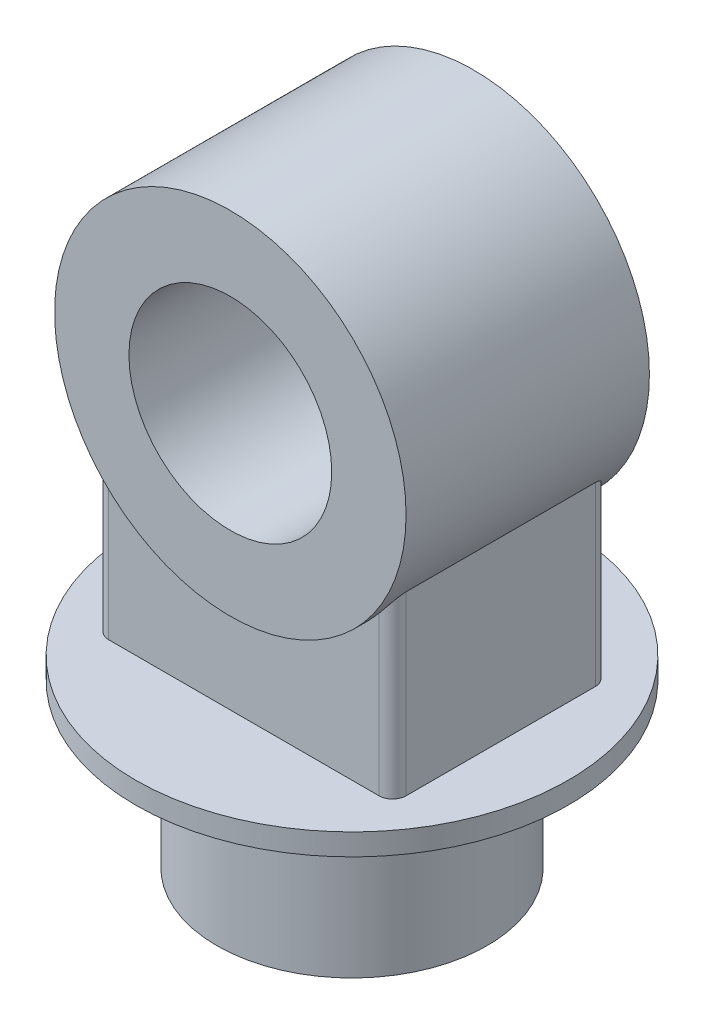
SolidWorks part; units mm, degrees
ref_plane "Front Plane" through (0, 0, 0) normal (0, 0, 1) x (1, 0, 0)
ref_plane "Top Plane" through (0, 0, 0) normal (0, 1, 0) x (1, 0, 0)
ref_plane "Right Plane" through (0, 0, 0) normal (1, 0, 0) x (0, 0, -1)
sketch "Sketch1" plane through (0, 0, 0) normal (0, 1, 0) x (1, 0, 0)
  circle A0 centre (0, 0) radius 100
  dimension "D1" = 200
extrude "Boss-Extrude1" add sketch "Sketch1" along normal blind 120 contours A0
sketch "Sketch2" plane through (0, 120, 0) normal (0, 1, 0) x (1, 0, 0)
  circle A0 centre (0, 0) radius 160
  dimension "D1" = 320
extrude "Boss-Extrude2" add sketch "Sketch2" along normal blind 16
sketch "Sketch3" plane through (0, 0, 0) normal (0, 0, 1) x (1, 0, 0)
  line L0 (160, 136) -> (-160, 136) construction
  circle A1 centre (0, 336) radius 75
  circle A2 centre (0, 336) radius 130
  dimension "D1" = 150
  dimension "D2" = 260
  dimension "D3" = 200
extrude "Boss-Extrude3" add sketch "Sketch3" along normal mid plane 180 separate body
sketch "Sketch4" plane through (0, 136, 0) normal (0, 1, 0) x (1, 0, 0)
  line L1 (-110, 80) -> (110, 80)
  line L2 (-110, 80) -> (-110, -80)
  line L3 (-110, -80) -> (110, -80)
  line L4 (110, 80) -> (110, -80)
  line L5 (-110, 80) -> (110, -80) construction
  line L6 (-110, -80) -> (110, 80) construction
  point P0 (0, 0)
  dimension "D1" = 160
  dimension "D2" = 220
extrude "Boss-Extrude4" add sketch "Sketch4" along normal up to next
fillet "Fillet1" radius 10 4 edges at (110, 201.359, 80) (110, 201.359, -80) (-110, 201.359, -80) (-110, 201.359, 80)
